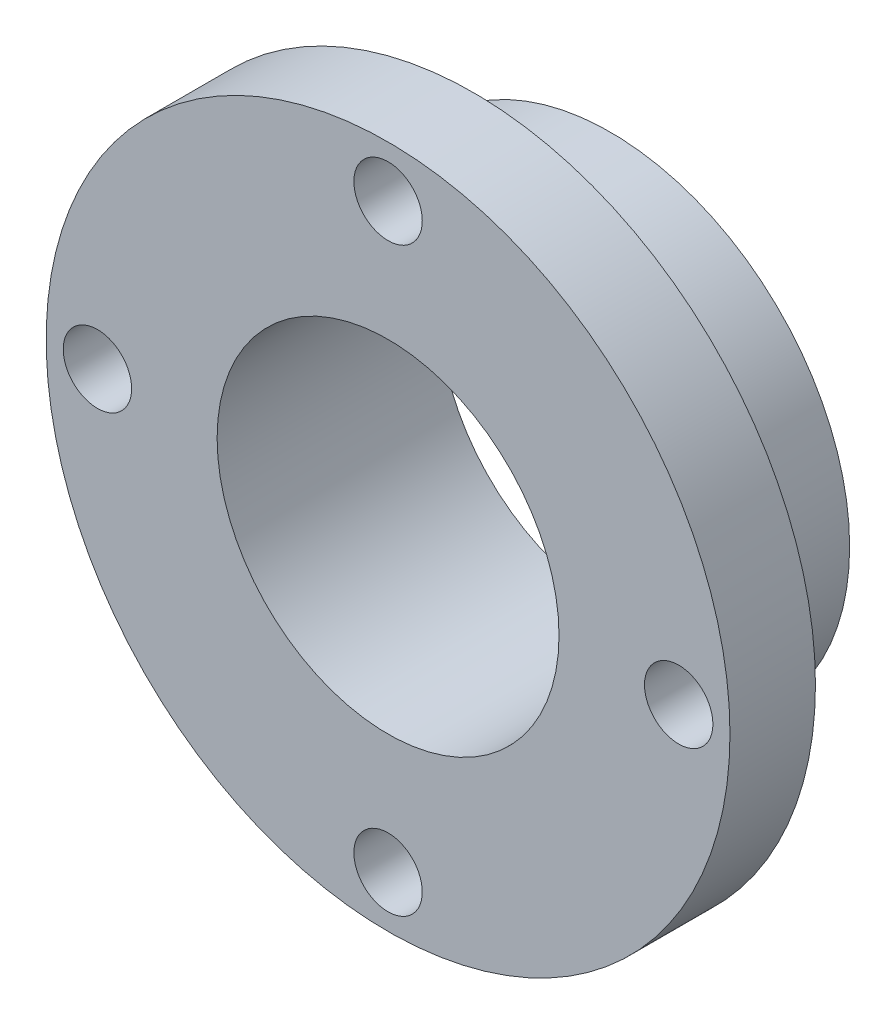
SolidWorks part; units mm, degrees
ref_plane "Front Plane" through (0, 0, 0) normal (0, 0, 1) x (1, 0, 0)
ref_plane "Top Plane" through (0, 0, 0) normal (0, 1, 0) x (1, 0, 0)
ref_plane "Right Plane" through (0, 0, 0) normal (1, 0, 0) x (0, 0, -1)
sketch "Sketch1" plane through (0, 0, 0) normal (0, 0, 1) x (1, 0, 0)
  circle A0 centre (0, 0) radius 10
  circle A1 centre (0, 0) radius 20
  dimension "D1" = 20
  dimension "D2" = 10
extrude "Boss-Extrude1" add sketch "Sketch1" along normal blind 5
sketch "Sketch2" plane through (0, 0, 0) normal (0, 0, -1) x (-1, 0, 0)
  circle A1 centre (0, 0) radius 10
  circle A2 centre (0, 0) radius 14
  circle A3 centre (0, 0) radius 14
  dimension "D1" = 4
extrude "Boss-Extrude2" add sketch "Sketch2" along normal blind 8
fillet "Fillet1" radius 1 1 edges at (14, 0, 0)
sketch "Sketch3" plane through (0, 0, 0) normal (0, 0, -1) x (-1, 0, 0)
  line L0 (0, 0) -> (0, 17) construction
  circle A0 centre (0, 17) radius 2
  dimension "D2" = 4
  dimension "D1" = 17
extrude "Cut-Extrude1" cut sketch "Sketch3" against normal blind 10 contours A0
pattern_circular "CirPattern1" count 4 over 360 about axis through (0, 0, 0) along (0, 0, 1) of "Cut-Extrude1"
